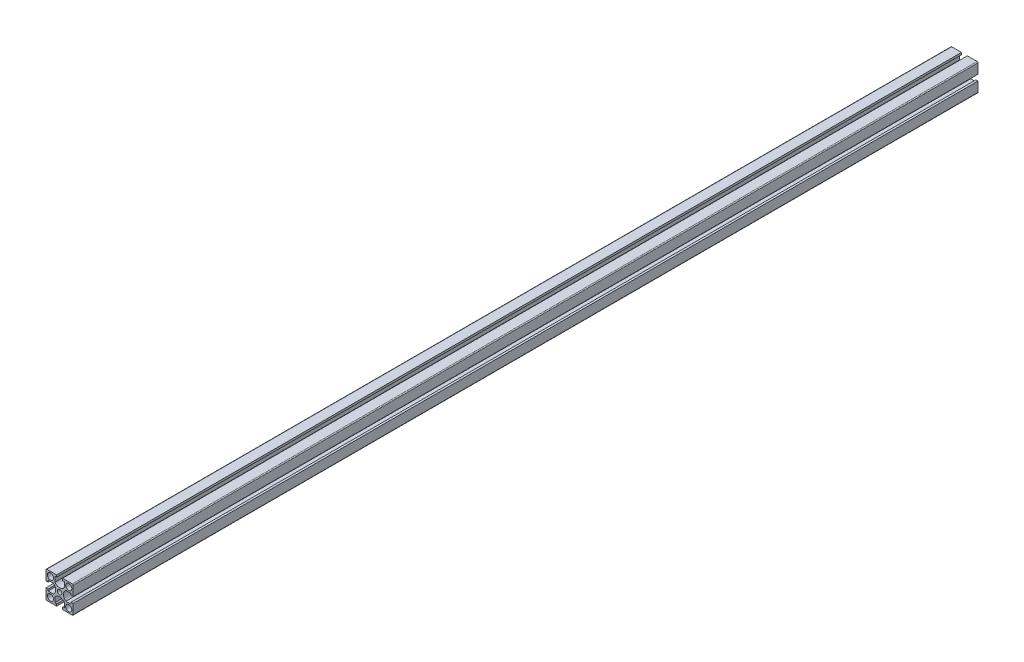
SolidWorks part; units mm, degrees
ref_plane "前视基准面" through (0, 0, 0) normal (0, 0, 1) x (1, 0, 0)
ref_plane "上视基准面" through (0, 0, 0) normal (0, 1, 0) x (1, 0, 0)
ref_plane "右视基准面" through (0, 0, 0) normal (1, 0, 0) x (0, 0, -1)
sketch "草图1" plane through (0, 0, 0) normal (0, 0, 1) x (1, 0, 0)
  line L0 (-2.7982, -17.2273) -> (7.9518, -17.2273)
  line L1 (8.9518, -16.2273) -> (8.9518, -5.4773)
  line L2 (-11.2482, -14.9273) -> (-9.2982, -14.9273)
  line L3 (-2.7982, -14.9273) -> (-0.8482, -14.9273)
  line L4 (-2.7982, -14.9273) -> (-2.7982, -17.2273)
  line L5 (-9.2982, -14.9273) -> (-9.2982, -17.2273)
  line L6 (-0.8482, -14.9273) -> (-0.8482, -9.1273)
  line L7 (-11.2482, -14.9273) -> (-11.2482, -9.1273)
  line L8 (-9.2982, -17.2273) -> (-20.0482, -17.2273)
  line L9 (-21.0482, -16.2273) -> (-21.0482, -5.4773)
  line L10 (-18.7482, -7.4273) -> (-18.7482, -5.4773)
  line L11 (-18.7482, -5.4773) -> (-21.0482, -5.4773)
  line L12 (-18.7482, -7.4273) -> (-12.9482, -7.4273)
  line L13 (-2.7982, 12.7727) -> (7.9518, 12.7727)
  line L14 (8.9518, 11.7727) -> (8.9518, 1.0227)
  line L15 (-11.2482, 10.4727) -> (-9.2982, 10.4727)
  line L16 (-2.7982, 10.4727) -> (-0.8482, 10.4727)
  line L17 (-2.7982, 10.4727) -> (-2.7982, 12.7727)
  line L18 (-9.2982, 10.4727) -> (-9.2982, 12.7727)
  line L19 (-0.8482, 10.4727) -> (-0.8482, 4.6727)
  line L20 (-11.2482, 10.4727) -> (-11.2482, 4.6727)
  line L21 (-9.2982, 12.7727) -> (-20.0482, 12.7727)
  line L22 (-21.0482, 11.7727) -> (-21.0482, 1.0227)
  line L23 (-18.7482, 2.9727) -> (-18.7482, 1.0227)
  line L24 (-18.7482, 1.0227) -> (-21.0482, 1.0227)
  line L25 (-18.7482, 2.9727) -> (-12.9482, 2.9727)
  line L26 (6.6518, -7.4273) -> (6.6518, -5.4773)
  line L27 (6.6518, -5.4773) -> (8.9518, -5.4773)
  line L28 (6.6518, -7.4273) -> (0.8518, -7.4273)
  line L29 (6.6518, 2.9727) -> (6.6518, 1.0227)
  line L30 (6.6518, 1.0227) -> (8.9518, 1.0227)
  line L31 (6.6518, 2.9727) -> (0.8518, 2.9727)
  arc A0 (7.9518, -17.2273) -> (8.9518, -16.2273) centre (7.9518, -16.2273) ccw
  circle A1 centre (-6.0482, -2.2273) radius 2.5
  circle A2 centre (-16.1482, -12.3273) radius 3.4
  circle A3 centre (4.0518, -12.3273) radius 3.4
  circle A4 centre (4.0518, 7.8727) radius 3.4
  circle A5 centre (-16.1482, 7.8727) radius 3.4
  arc A6 (-0.8482, -9.1273) -> (-11.2482, -9.1273) centre (-6.0482, -13.0273) ccw
  arc A7 (-21.0482, -16.2273) -> (-20.0482, -17.2273) centre (-20.0482, -16.2273) ccw
  arc A8 (-12.9482, -7.4273) -> (-12.9482, 2.9727) centre (-16.8482, -2.2273) ccw
  arc A9 (8.9518, 11.7727) -> (7.9518, 12.7727) centre (7.9518, 11.7727) ccw
  arc A10 (-11.2482, 4.6727) -> (-0.8482, 4.6727) centre (-6.0482, 8.5727) ccw
  arc A11 (-20.0482, 12.7727) -> (-21.0482, 11.7727) centre (-20.0482, 11.7727) ccw
  arc A12 (0.8518, 2.9727) -> (0.8518, -7.4273) centre (4.7518, -2.2273) ccw
extrude "凸台-拉伸1" add sketch "草图1" along normal blind 1000
